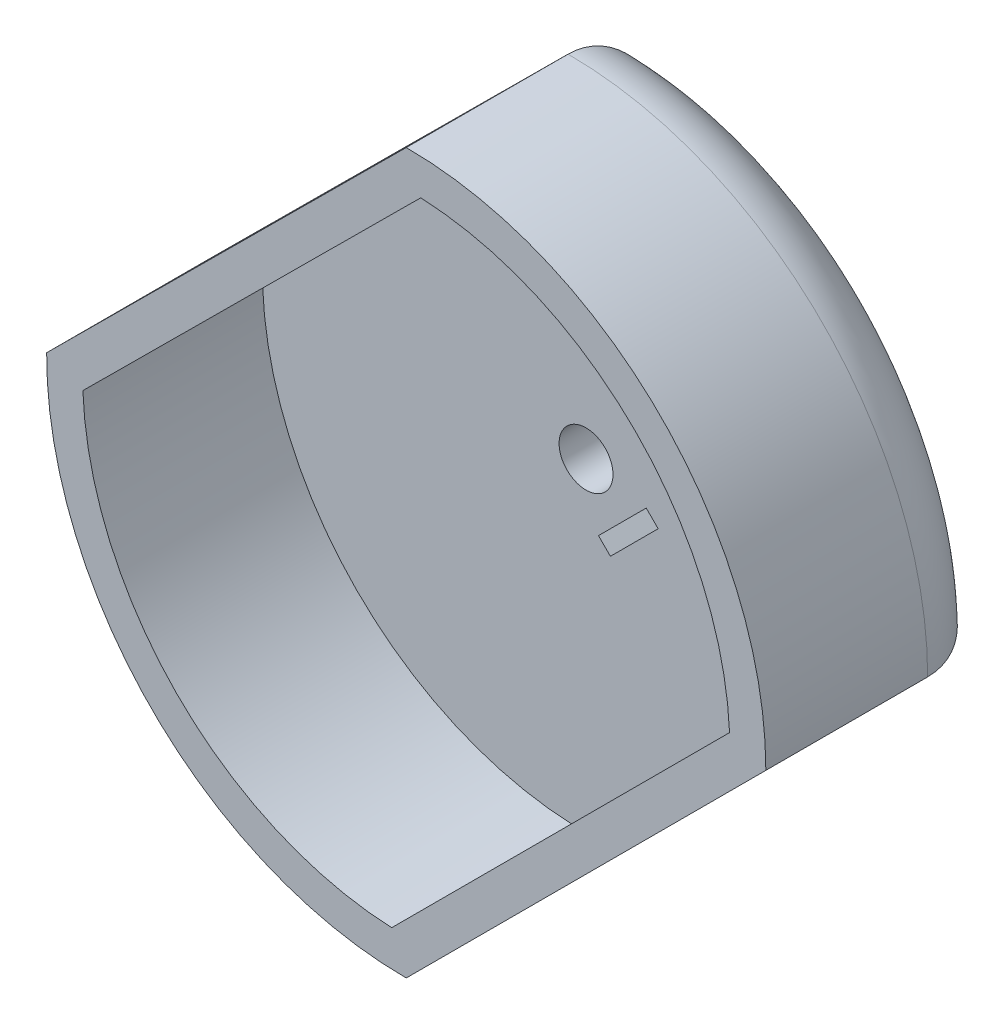
SolidWorks part; units mm, degrees
ref_plane "Front Plane" through (0, 0, 0) normal (0, 0, 1) x (1, 0, 0)
ref_plane "Top Plane" through (0, 0, 0) normal (0, 1, 0) x (1, 0, 0)
ref_plane "Right Plane" through (0, 0, 0) normal (1, 0, 0) x (0, 0, -1)
sketch "Sketch1" plane through (0, 0, 0) normal (0, 0, 1) x (1, 0, 0)
  line L0 (0, 10) -> (-9.9998, 0.0595)
  line L1 (0.4034, 8.991) -> (-8.9932, -0.3499)
  line L2 (10, 0) -> (0, -10)
  line L3 (8.9909, 0.4051) -> (-0.4051, -8.9909)
  arc A0 (-9.9998, 0.0595) -> (0, -10) centre (0, 0) ccw
  arc A1 (10, 0) -> (0, 10) centre (0, 0) ccw
  arc A2 (-8.9932, -0.3499) -> (-0.4051, -8.9909) centre (0, 0) ccw
  arc A3 (8.9909, 0.4051) -> (0.4034, 8.991) centre (0, 0) ccw
  dimension "D1" = 20
  dimension "D2" = 14.1
  dimension "D3" = 1
extrude "Boss-Extrude1" add sketch "Sketch1" along normal blind 5
sketch "Sketch2" plane through (0, 0, 0) normal (0, 0, -1) x (-1, 0, 0)
  line L0 (0, 10) -> (9.9998, 0.0595) construction
  line L1 (0, -10) -> (-10, 0) construction
  line L2 (0, 10) -> (9.9998, 0.0595)
  line L3 (0, -10) -> (-10, 0)
  arc A0 (0, 10) -> (-10, 0) centre (0, 0) ccw construction
  arc A1 (0, -10) -> (9.9998, 0.0595) centre (0, 0) ccw construction
  arc A2 (0, 10) -> (-10, 0) centre (0, 0) ccw
  arc A3 (0, -10) -> (9.9998, 0.0595) centre (0, 0) ccw
extrude "Boss-Extrude2" add sketch "Sketch2" along normal blind 1.5
fillet "Fillet1" radius 2 4 edges at (7.0711, 7.0711, -1.5) (-7.0921, -7.05, -1.5) (5, -5, -1.5) (-4.9999, 5.0298, -1.5)
sketch "Sketch3" plane through (0, 0, -1.5) normal (0, 0, -1) x (-1, 0, 0)
  line L0 (0, 2.8547) -> (2.8547, 0)
  arc A0 (0, 2.8547) -> (2.8547, 0) centre (0, 0) ccw
extrude "Boss-Extrude3" add sketch "Sketch3" along normal blind 1.5
sketch "Sketch4" plane through (0, 0, -3) normal (0, 0, -1) x (-1, 0, 0)
  line L0 (0, 0) -> (-2.0186, -2.0186) construction
  line L1 (-1.6735, -0.3451) -> (-0.3451, -1.6735)
  line L2 (-0.3451, -1.6735) -> (-0.6772, -2.0055)
  line L3 (-0.6772, -2.0055) -> (-2.0055, -0.6772)
  line L4 (-1.6735, -0.3451) -> (-2.0055, -0.6772)
  circle A0 centre (0, 0) radius 0.75
  arc A1 (0, 2.8547) -> (2.8547, 0) centre (0, 0) ccw construction
  point P12 (-1.3414, -1.3414)
  point P13 (-1.0093, -1.0093)
  dimension "D1" = 1.5
extrude "Cut-Extrude1" cut sketch "Sketch4" against normal through all
sketch "Sketch5" plane through (5, -5, 0) normal (0.7071, -0.7071, 0) x (0, 0, -1)
  line L0 (-2.6763, 0) -> (-5, 0) construction
  line L1 (-5, -7.0711) -> (-5, 7.0711) construction
  line L2 (-1.6446, -2.44) -> (-3.4325, -2.44)
  line L3 (-3.4325, -2.44) -> (-3.4325, -3.1005)
  line L4 (-3.4325, -3.1005) -> (-1.6446, -3.1005)
  line L5 (-1.6446, -3.1005) -> (-1.6446, -2.44)
  line L6 (-3.4325, 2.44) -> (-3.4325, 3.1005)
  line L7 (-1.6446, 2.44) -> (-3.4325, 2.44)
  line L8 (-1.6446, 3.1005) -> (-1.6446, 2.44)
  line L9 (-3.4325, 3.1005) -> (-1.6446, 3.1005)
extrude "Cut-Extrude2" cut sketch "Sketch5" against normal blind 1
fillet "Fillet2" radius 0.5 2 edges at (-1.4273, 1.4273, -3) (2.0186, -2.0186, -3)
